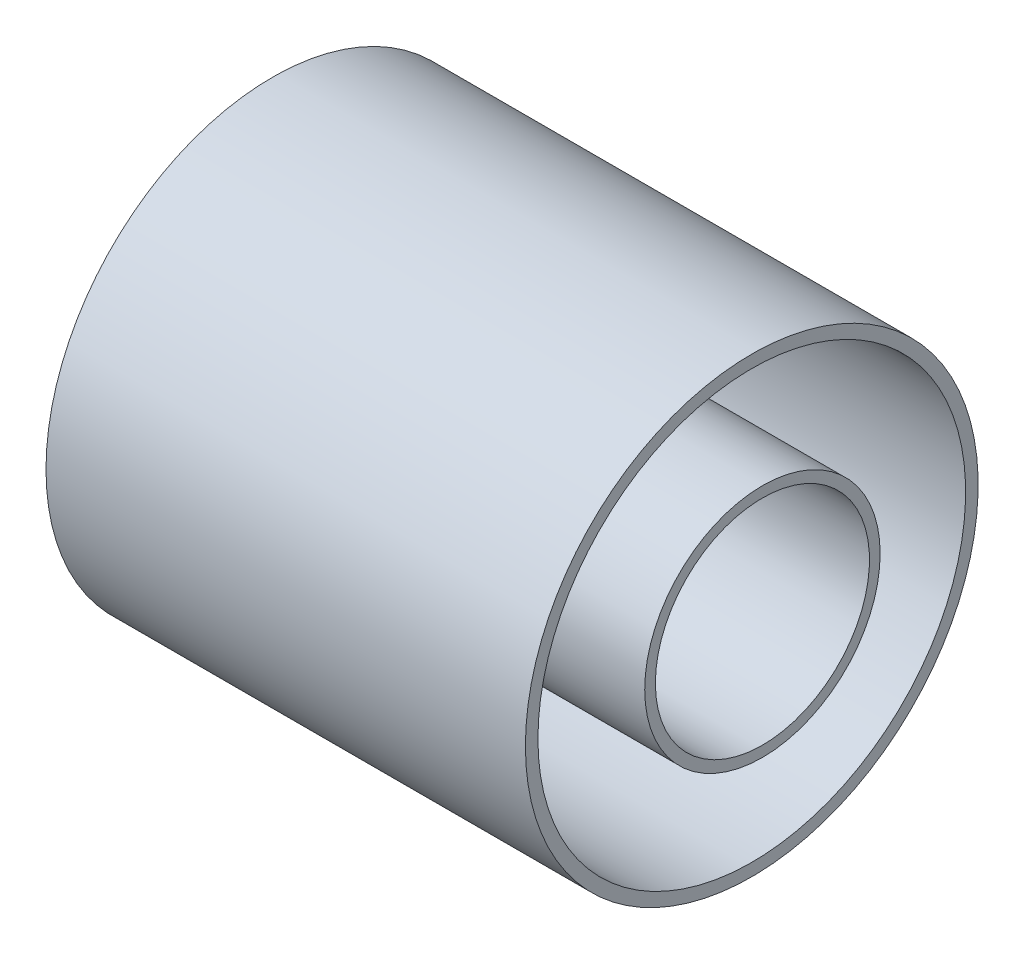
SolidWorks part; units mm, degrees
ref_plane "Front Plane" through (0, 0, 0) normal (0, 0, 1) x (1, 0, 0)
ref_plane "Top Plane" through (0, 0, 0) normal (0, 1, 0) x (1, 0, 0)
ref_plane "Right Plane" through (0, 0, 0) normal (1, 0, 0) x (0, 0, -1)
sketch "Sketch2" plane through (0, 0, 0) normal (0, 0, 1) x (1, 0, 0)
  line L0 (0, 0) -> (51.3521, 0)
  line L1 (-57.9111, 25.527) -> (63.9581, 25.527)
  line L2 (-57.9111, 28.067) -> (63.9581, 28.067)
  line L3 (-52.8819, 50.9905) -> (61.4181, 50.9905)
  line L4 (-52.8819, 53.975) -> (61.4181, 53.975)
  line L5 (61.4181, 53.975) -> (61.4181, 50.9905)
  line L6 (-52.8819, 53.975) -> (-52.8819, 50.9905)
  line L7 (-57.9111, 28.067) -> (-57.9111, 25.527)
  line L8 (63.9581, 28.067) -> (63.9581, 25.527)
  point P11 (63.9581, 26.797)
  dimension "D1" = 2.54
  dimension "D2" = 2.9845
  dimension "D3" = 25.527
  dimension "D4" = 50.9905
  dimension "D5" = 121.8692
  dimension "D7" = 5.0292
  dimension "D8" = 2.54
revolve "Revolve1" add sketch "Sketch2" angle 360 about L0
